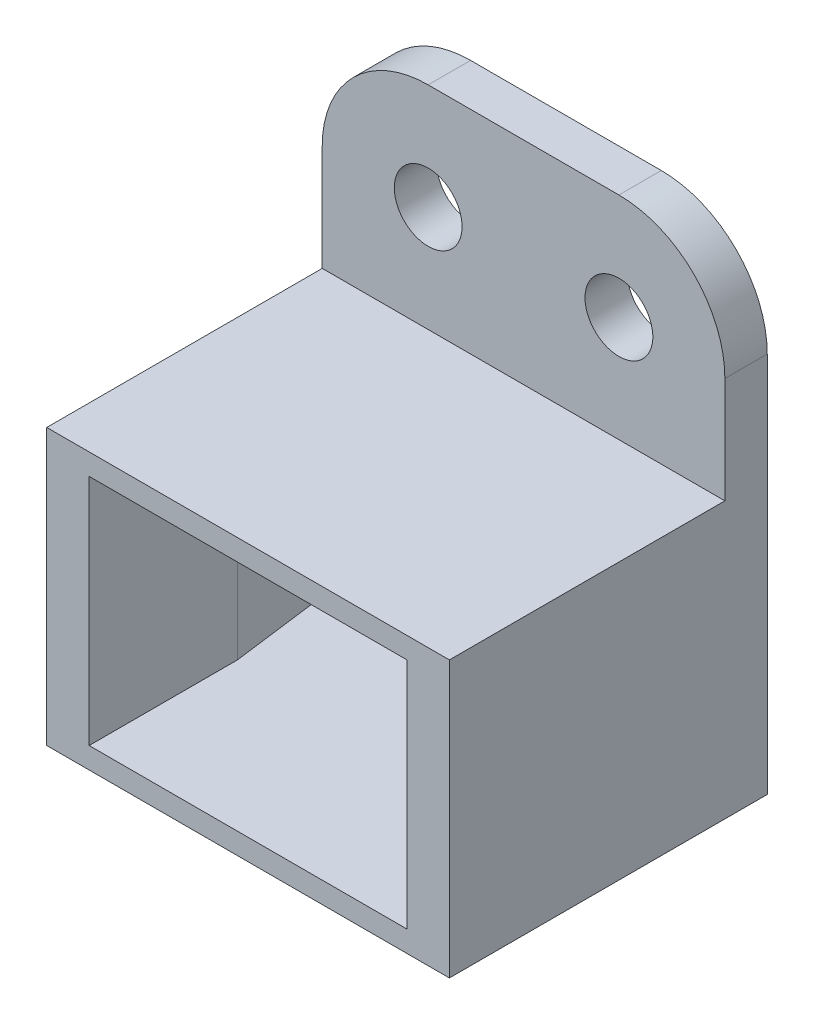
SolidWorks part; units mm, degrees
ref_plane "Front Plane" through (0, 0, 0) normal (0, 0, 1) x (1, 0, 0)
ref_plane "Top Plane" through (0, 0, 0) normal (0, 1, 0) x (1, 0, 0)
ref_plane "Right Plane" through (0, 0, 0) normal (1, 0, 0) x (0, 0, -1)
sketch "Sketch1" plane through (0, 0, 0) normal (0, 0, 1) x (1, 0, 0)
  line L5 (-15, -11) -> (15, -11)
  line L6 (-15, -11) -> (-15, 11)
  line L7 (-15, 11) -> (15, 11)
  line L8 (15, -11) -> (15, 11)
  line L9 (-15, -11) -> (15, 11) construction
  line L10 (-15, 11) -> (15, -11) construction
  line L11 (19, -13) -> (-19, -13)
  line L12 (19, -13) -> (19, 13)
  line L13 (19, 13) -> (-19, 13)
  line L14 (-19, -13) -> (-19, 13)
  line L15 (19, -13) -> (-19, 13) construction
  line L16 (19, 13) -> (-19, -13) construction
  point P0 (0, 0)
  point P5 (0, 0)
  dimension "D1" = 22
  dimension "D2" = 30
  dimension "D3" = 2
  dimension "D4" = 4
extrude "Boss-Extrude1" add sketch "Sketch1" along normal blind 30
sketch "Sketch2" plane through (0, 11, 0) normal (0, -1, 0) x (1, 0, 0)
  line L0 (15, 0) -> (16.5, 4.5)
  line L1 (16.5, 4.5) -> (15, 16)
  line L2 (15, 30) -> (15, 0) construction
  line L3 (15, 16) -> (15, 0)
  line L4 (0, 0) -> (0, 30) construction
  line L5 (15, 0) -> (-15, 0) construction
  line L6 (15, 30) -> (-15, 30) construction
  line L7 (-15, 16) -> (-15, 0)
  line L8 (-16.5, 4.5) -> (-15, 16)
  line L9 (-15, 0) -> (-16.5, 4.5)
  dimension "D1" = 4.5
  dimension "D2" = 16
  dimension "D3" = 1.5
extrude "Cut-Extrude1" cut sketch "Sketch2" along normal up to surface (22 mm away) up to face at (0, -11, 15)
sketch "Sketch3" plane through (0, 0, 0) normal (0, 0, -1) x (-1, 0, 0)
  line L0 (-19, -13) -> (-19, 13) construction
  line L1 (19, 13) -> (-19, 13)
  line L2 (19, 13) -> (19, 23)
  line L3 (9, 33) -> (-9, 33)
  line L4 (-19, 13) -> (-19, 23)
  arc A0 (19, 23) -> (9, 33) centre (9, 23) ccw
  arc A1 (-9, 33) -> (-19, 23) centre (-9, 23) ccw
  circle A2 centre (-9, 23) radius 3.2
  circle A3 centre (9, 23) radius 3.2
  point P11 (-19, 33)
  dimension "D2" = 10
  dimension "D1" = 20
extrude "Boss-Extrude2" add sketch "Sketch3" against normal blind 4
sketch "Sketch4" plane through (19, 0, 0) normal (1, 0, 0) x (0, 0, -1)
  line L0 (-30, -13) -> (-30, 13) construction
  line L1 (-30, 11) -> (-27, 11)
  line L2 (-30, 11) -> (-30, 7)
  line L3 (-30, 7) -> (-27, 7)
  line L4 (-27, 11) -> (-27, 7)
  line L5 (-30, 13) -> (-4, 13) construction
  dimension "D1" = 4
  dimension "D2" = 3
  dimension "D3" = 2
